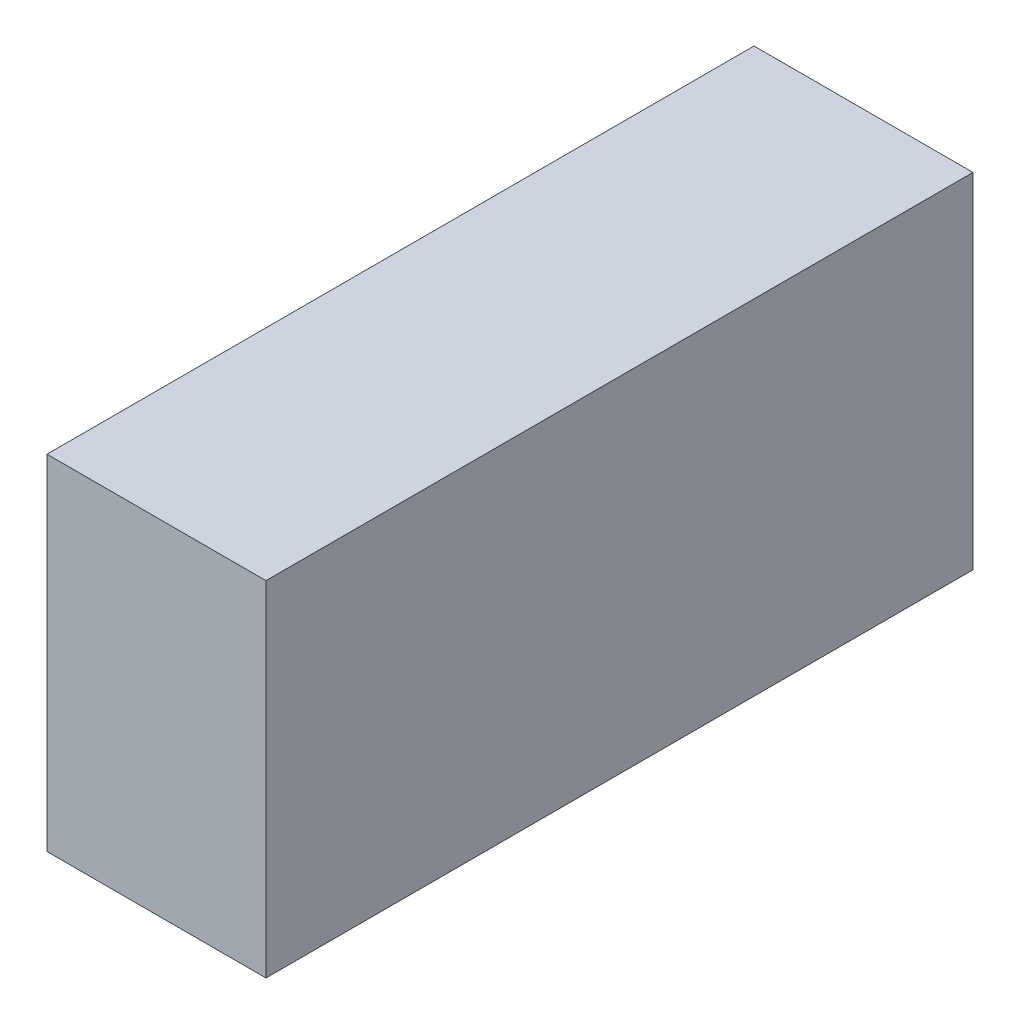
SolidWorks part; units mm, degrees
ref_plane "Front Plane" through (0, 0, 0) normal (0, 0, 1) x (1, 0, 0)
ref_plane "Top Plane" through (0, 0, 0) normal (0, 1, 0) x (1, 0, 0)
ref_plane "Right Plane" through (0, 0, 0) normal (1, 0, 0) x (0, 0, -1)
sketch "Sketch1" plane through (0, 0, 0) normal (0, 0, 1) x (1, 0, 0)
  line L1 (-17.5, -27.5) -> (17.5, -27.5)
  line L2 (-17.5, -27.5) -> (-17.5, 27.5)
  line L3 (-17.5, 27.5) -> (17.5, 27.5)
  line L4 (17.5, -27.5) -> (17.5, 27.5)
  line L5 (-17.5, -27.5) -> (17.5, 27.5) construction
  line L6 (-17.5, 27.5) -> (17.5, -27.5) construction
  point P0 (0, 0)
  dimension "D1" = 55
  dimension "D2" = 35
extrude "Boss-Extrude1" add sketch "Sketch1" along normal mid plane 113
